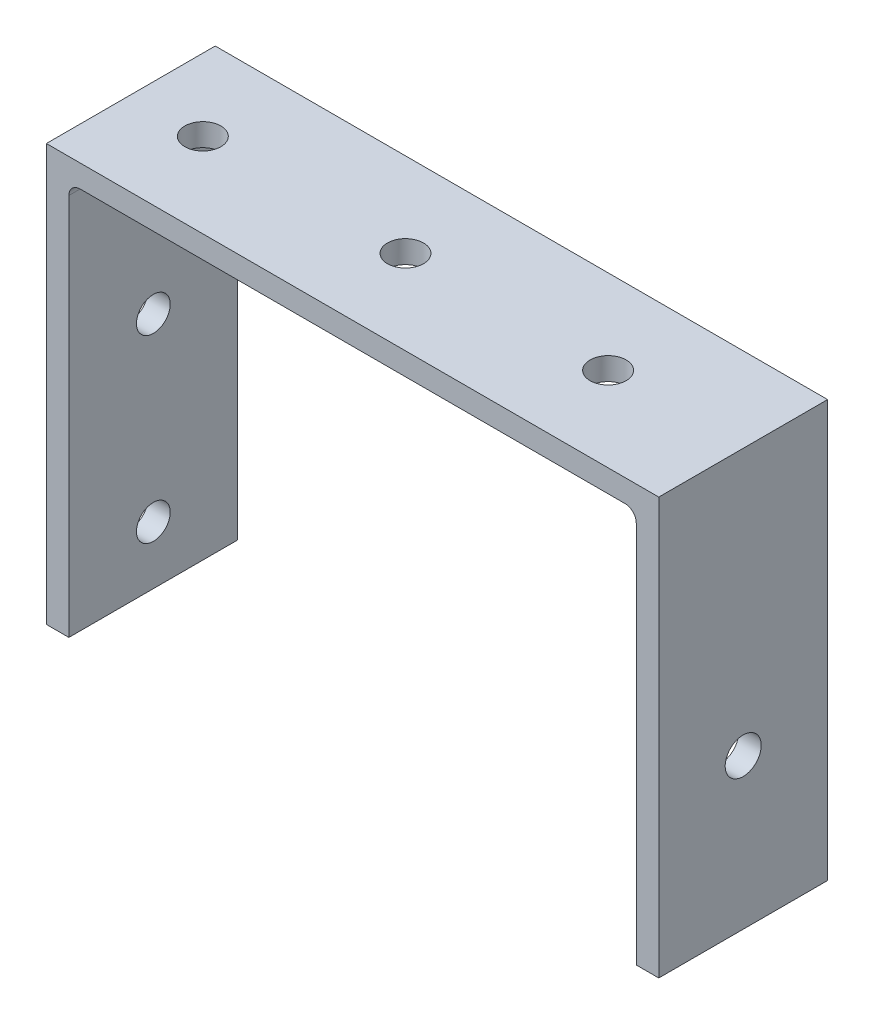
SolidWorks part; units mm, degrees
ref_plane "Plan de face" through (0, 0, 0) normal (0, 0, 1) x (1, 0, 0)
ref_plane "Plan de dessus" through (0, 0, 0) normal (0, 1, 0) x (1, 0, 0)
ref_plane "Plan de droite" through (0, 0, 0) normal (1, 0, 0) x (0, 0, -1)
sketch "Esquisse1" plane through (0, 0, 0) normal (0, 1, 0) x (1, 0, 0)
  line L0 (0, 0) -> (0, 15)
  line L1 (0, 15) -> (54.4, 15)
  line L2 (54.4, 15) -> (54.4, 0)
  line L3 (54.4, 0) -> (0, 0)
  dimension "D1" = 54.4
  dimension "D2" = 15
extrude "Boss.-Extru.1" add sketch "Esquisse1" along normal blind 2
sketch "Esquisse2" plane through (0, 0, 0) normal (0, -1, 0) x (1, 0, 0)
  line L0 (0, 0) -> (2, 0)
  line L1 (0, 0) -> (54.4, 0) construction
  line L2 (2, 0) -> (2, -15)
  line L3 (54.4, -15) -> (0, -15) construction
  line L4 (2, -15) -> (0, -15)
  line L5 (0, -15) -> (0, 0)
  line L6 (27.2, 0) -> (27.2, -15) construction
  line L7 (54.4, -15) -> (54.4, 0)
  line L8 (52.4, -15) -> (54.4, -15)
  line L9 (52.4, 0) -> (52.4, -15)
  line L10 (54.4, 0) -> (52.4, 0)
  dimension "D1" = 2
extrude "Boss.-Extru.2" add sketch "Esquisse2" along normal blind 35
fillet "Congé1" radius 1 2 edges at (52.4, 0, -7.5)
sketch "Esquisse3" plane through (54.4, 0, 0) normal (1, 0, 0) x (0, 0, -1)
  line L0 (7.5, 2) -> (7.5, -35) construction
  line L1 (0, 2) -> (15, 2) construction
  line L2 (15, -35) -> (0, -35) construction
  circle A0 centre (7.5, -21.65) radius 1.6
  dimension "D1" = 3.2
  dimension "D2" = 13.35
extrude "Enlèv. mat.-Extru.1" cut sketch "Esquisse3" against normal up to next
sketch "Esquisse4" plane through (0, 2, 0) normal (0, 1, 0) x (1, 0, 0)
  line L0 (0, 7.5) -> (54.4, 7.5) construction
  line L1 (0, 15) -> (0, 0) construction
  line L2 (54.4, 0) -> (54.4, 15) construction
  circle A0 centre (42.4, 7.5) radius 1.6
  circle A1 centre (6.4, 7.5) radius 1.6
  circle A2 centre (24.4, 7.5) radius 1.6
  dimension "D1" = 3.2
  dimension "D2" = 12
  dimension "D3" = 18
  dimension "D4" = 18
extrude "Enlèv. mat.-Extru.2" cut sketch "Esquisse4" against normal up to next
sketch "Esquisse5" plane through (0, -35, 0) normal (0, -1, 0) x (1, 0, 0)
  line L0 (0, 0) -> (2, 0)
  line L1 (2, 0) -> (2, -15)
  line L2 (2, -15) -> (0, -15)
  line L3 (0, -15) -> (0, 0)
sketch "Esquisse6" plane through (0, 0, 0) normal (-1, 0, 0) x (0, 0, 1)
  line L0 (-7.5, 2) -> (-7.5, -35) construction
  line L1 (-15, 2) -> (0, 2) construction
  line L2 (0, -35) -> (-15, -35) construction
  circle A0 centre (-7.5, -13.86) radius 1.5
  circle A1 centre (-7.5, -29.86) radius 1.5
  dimension "D1" = 3
  dimension "D2" = 15.86
  dimension "D3" = 16
  dimension "D4" = 7.5
extrude "Enlèv. mat.-Extru.3" cut sketch "Esquisse6" against normal up to next
